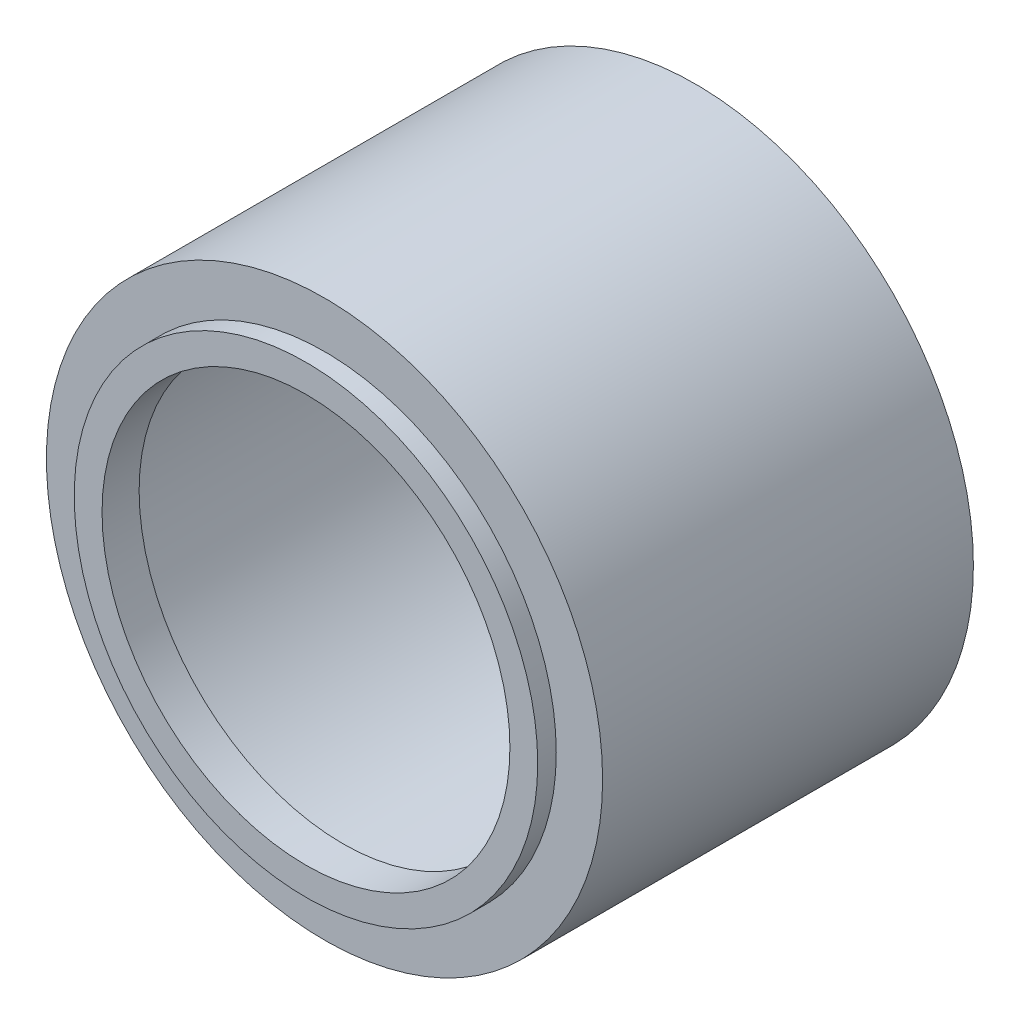
SolidWorks part; units mm, degrees
ref_plane "Plan de face" through (0, 0, 0) normal (0, 0, 1) x (1, 0, 0)
ref_plane "Plan de dessus" through (0, 0, 0) normal (0, 1, 0) x (1, 0, 0)
ref_plane "Plan de droite" through (0, 0, 0) normal (1, 0, 0) x (0, 0, -1)
sketch "Esquisse1" plane through (0, 0, 0) normal (0, 0, 1) x (1, 0, 0)
  circle A0 centre (0, 0) radius 15
extrude "Boss.-Extru.1" add sketch "Esquisse1" along normal blind 20
sketch "Esquisse3" plane through (0, 0, 0) normal (0, 0, -1) x (-1, 0, 0)
  circle A0 centre (0, 0) radius 13.5
extrude "Enlèv. mat.-Extru.2" cut sketch "Esquisse3" against normal blind 19
sketch "Esquisse4" plane through (0, 0, 20) normal (0, 0, 1) x (1, 0, 0)
  circle A0 centre (0, 0) radius 12.5
extrude "Boss.-Extru.2" add sketch "Esquisse4" along normal blind 1
sketch "Esquisse5" plane through (0, 0, 21) normal (0, 0, 1) x (1, 0, 0)
  circle A0 centre (0, 0) radius 11
extrude "Enlèv. mat.-Extru.3" cut sketch "Esquisse5" against normal blind 2
